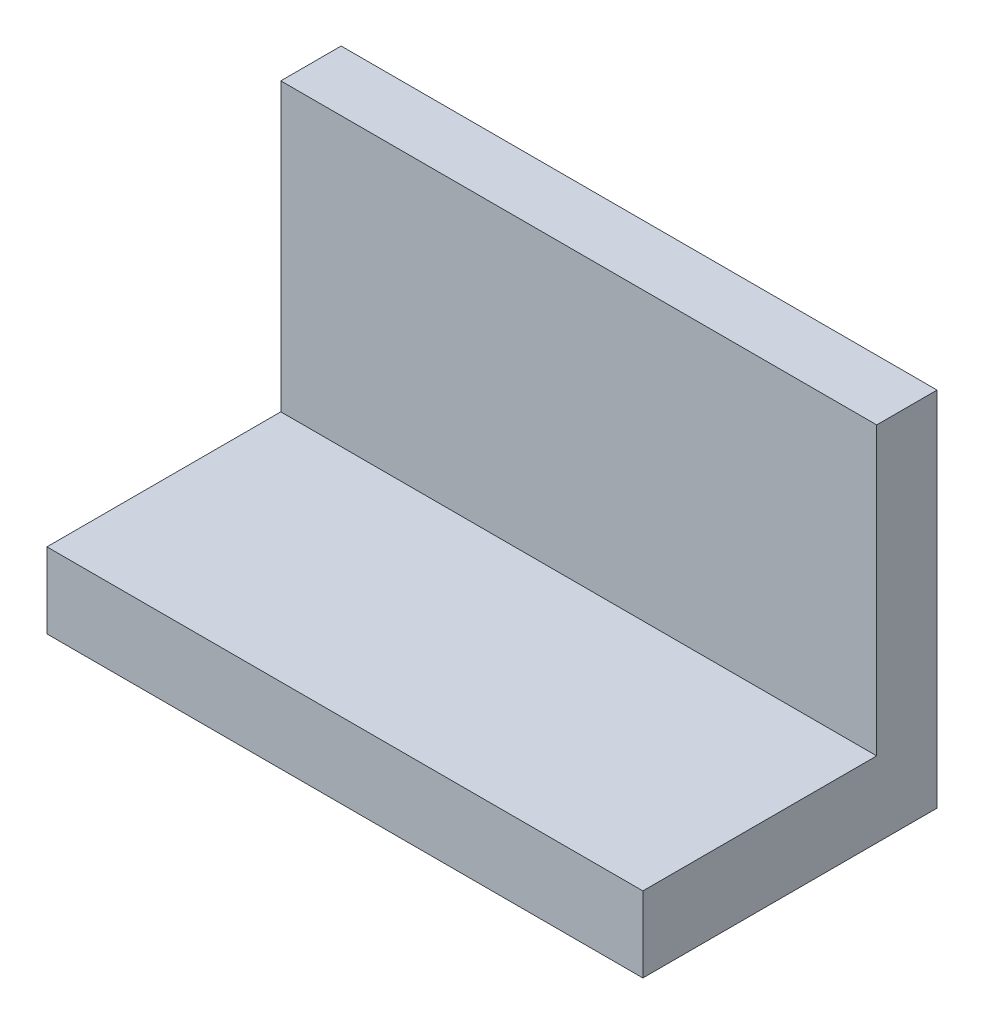
SolidWorks part; units mm, degrees
ref_plane "Спереди" through (0, 0, 0) normal (0, 0, 1) x (1, 0, 0)
ref_plane "Сверху" through (0, 0, 0) normal (0, 1, 0) x (1, 0, 0)
ref_plane "Справа" through (0, 0, 0) normal (1, 0, 0) x (0, 0, -1)
sketch "Эскиз1" plane through (0, 0, 0) normal (0, 1, 0) x (1, 0, 0)
  line L1 (7.9, -3.9) -> (-7.9, -3.9)
  line L2 (7.9, -3.9) -> (7.9, 3.9)
  line L3 (7.9, 3.9) -> (-7.9, 3.9)
  line L4 (-7.9, -3.9) -> (-7.9, 3.9)
  line L5 (7.9, -3.9) -> (-7.9, 3.9) construction
  line L6 (7.9, 3.9) -> (-7.9, -3.9) construction
  point P0 (0, 0)
  dimension "D1" = 15.8
  dimension "D2" = 7.8
extrude "Бобышка-Вытянуть1" add sketch "Эскиз1" along normal blind 9.6
sketch "Эскиз2" plane through (0, 9.6, 0) normal (0, 1, 0) x (1, 0, 0)
  line L0 (-7.9, 3.9) -> (-7.9, -3.9) construction
  line L1 (-7.9, 2.3) -> (7.9, 2.3)
  line L2 (-7.9, 2.3) -> (-7.9, -3.9)
  line L3 (-7.9, -3.9) -> (7.9, -3.9)
  line L4 (7.9, 2.3) -> (7.9, -3.9)
  line L5 (7.9, 3.9) -> (-7.9, 3.9) construction
  dimension "D1" = 1.6
extrude "Вырез-Вытянуть1" cut sketch "Эскиз2" against normal blind 7.6
sketch "Эскиз3" plane through (0, 0, 0) normal (0, -1, 0) x (1, 0, 0)
  line L0 (-7.9, 3.9) -> (7.9, 3.9) construction
  line L2 (-7.9, -3.9) -> (-7.9, 3.9) construction
  circle A0 centre (-4, 0) radius 2.5
  circle A1 centre (3.874, 0) radius 2.5
  dimension "D3" = 2
  dimension "D1" = 3.9
  dimension "D2" = 3.9
extrude "Вырез-Вытянуть2" cut sketch "Эскиз3" against normal blind 1.8
